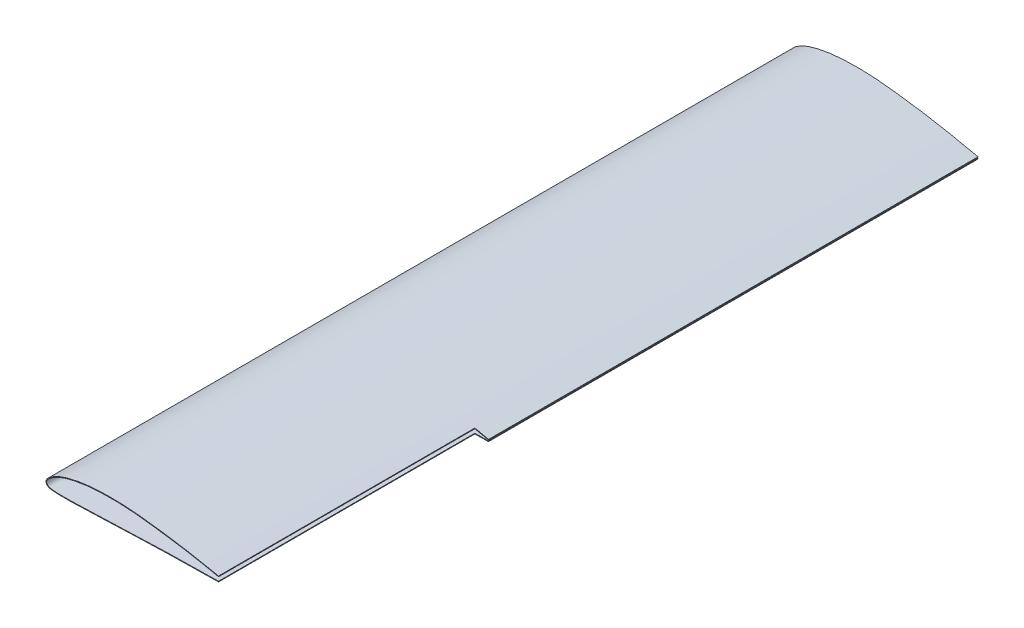
SolidWorks part; units mm, degrees
material "轻木"
ref_plane "前视基准面" through (0, 0, 0) normal (0, 0, 1) x (1, 0, 0)
ref_plane "上视基准面" through (0, 0, 0) normal (0, 1, 0) x (1, 0, 0)
ref_plane "右视基准面" through (0, 0, 0) normal (1, 0, 0) x (0, 0, -1)
other "Configuration Table"
sketch "草图2" plane through (0, 0, 0) normal (0, 0, 1) x (1, 0, 0)
  line L0 (152.0922, -4.0096) -> (151.8745, -4.9856)
  line L1 (151.8745, -6.1918) -> (151.8782, -7.1918)
  spline S0 degree 3 poles (2527.2793, 5171.2522) (1224.3818, -581.4504) (698.4321, -111.6596) (97.5228, 6.3509) (79.323, 9.677) (61.0574, 12.5697) (42.7251, 15.1223) (24.3777, 17.5567) (6.0024, 19.6713) (-12.4132, 21.2419) (-30.8708, 21.8741) (-49.3536, 21.6282) (-64.7221, 20.7846) (-76.9396, 19.4244) (-86.0445, 17.9962) (-95.0915, 16.1982) (-102.5435, 14.373) (-108.4281, 12.6438) (-112.7635, 11.1816) (-116.9506, 9.4061) (-121.0465, 7.338) (-125.0852, 5.1449) (-128.9853, 2.7585) (-131.9718, 0.5145) (-134.0254, -1.6013) (-135.3116, -3.3311) (-136.1565, -5.2223) (-136.2196, -7.0675) (-135.3796, -8.8735) (-133.9823, -10.403) (-132.2712, -11.4212) (-130.1979, -11.9075) (-127.9164, -12.2567) (-124.9055, -12.6448) (-121.1053, -12.9445) (-116.5159, -13.063) (-111.894, -13.0888) (-105.7281, -13.0822) (-98.0182, -13.0426) (-88.7886, -12.824) (-79.5455, -12.4149) (-70.2848, -12.0448) (-61.0289, -11.7236) (-48.6895, -11.3178) (-33.2723, -10.775) (-14.7708, -10.05) (3.7324, -9.2974) (22.2431, -8.606) (40.7587, -8.0244) (59.2779, -7.5768) (77.7911, -7.1821) (96.3085, -6.7893) (114.8357, -6.5452) (402.7621, -3.862) (691.0162, 21.319) (591.9409, -5930.9613) knots -2.852397 -2.852397 -2.852397 -2.852397 0.078237 0.108366 0.138495 0.168624 0.198753 0.228882 0.259011 0.28914 0.319269 0.349398 0.379527 0.394592 0.409656 0.424721 0.439785 0.447318 0.45485 0.462382 0.469915 0.477447 0.484979 0.492511 0.496277 0.500044 0.50381 0.507576 0.511342 0.515108 0.518874 0.52264 0.526407 0.530173 0.537705 0.545237 0.552769 0.560302 0.575366 0.590431 0.605495 0.62056 0.635624 0.650689 0.680818 0.710947 0.741076 0.771205 0.801334 0.831463 0.861593 0.891722 0.921851 0.95198 2.29766 2.29766 2.29766 2.29766 only from (151.8745, -4.9856) to (151.8745, -6.1918) construction
  spline S1 degree 3 poles (151.8745, -4.9856) (139.8319, -2.2996) (121.7361, 1.5957) (97.5228, 6.3509) (79.323, 9.677) (61.0574, 12.5697) (42.7251, 15.1223) (24.3777, 17.5567) (6.0024, 19.6713) (-12.4132, 21.2419) (-30.8708, 21.8741) (-49.3536, 21.6282) (-64.7221, 20.7846) (-76.9396, 19.4244) (-86.0445, 17.9962) (-95.0915, 16.1982) (-102.5435, 14.373) (-108.4281, 12.6438) (-112.7635, 11.1816) (-116.9506, 9.4061) (-121.0465, 7.338) (-125.0852, 5.1449) (-128.9853, 2.7585) (-131.9718, 0.5145) (-134.0254, -1.6013) (-135.3116, -3.3311) (-136.1565, -5.2223) (-136.2196, -7.0675) (-135.3796, -8.8735) (-133.9823, -10.403) (-132.2712, -11.4212) (-130.1979, -11.9075) (-127.9164, -12.2567) (-124.9055, -12.6448) (-121.1053, -12.9445) (-116.5159, -13.063) (-111.894, -13.0888) (-105.7281, -13.0822) (-98.0182, -13.0426) (-88.7886, -12.824) (-79.5455, -12.4149) (-70.2848, -12.0448) (-61.0289, -11.7236) (-48.6895, -11.3178) (-33.2723, -10.775) (-14.7708, -10.05) (3.7324, -9.2974) (22.2431, -8.606) (40.7587, -8.0244) (59.2779, -7.5768) (77.7911, -7.1821) (96.3085, -6.7893) (114.8357, -6.5452) (133.3464, -6.3727) (145.6993, -6.2144) (151.8745, -6.1918) knots 0.017978 0.017978 0.017978 0.017978 0.078237 0.108366 0.138495 0.168624 0.198753 0.228882 0.259011 0.28914 0.319269 0.349398 0.379527 0.394592 0.409656 0.424721 0.439785 0.447318 0.45485 0.462382 0.469915 0.477447 0.484979 0.492511 0.496277 0.500044 0.50381 0.507576 0.511342 0.515108 0.518874 0.52264 0.526407 0.530173 0.537705 0.545237 0.552769 0.560302 0.575366 0.590431 0.605495 0.62056 0.635624 0.650689 0.680818 0.710947 0.741076 0.771205 0.801334 0.831463 0.861593 0.891722 0.921851 0.95198 0.982109 0.982109 0.982109 0.982109
  spline S2 degree 1 poles (152.0922, -4.0096) (151.8782, -7.1918) knots 0 0 1 1 construction
  spline S3 degree 3 poles (152.0922, -4.0096) (140.0432, -1.3222) (121.9389, 2.575) (97.7101, 7.3332) (79.4922, 10.6627) (61.2022, 13.5592) (42.8597, 16.1132) (24.5027, 18.5489) (6.1053, 20.6662) (-12.3516, 22.2404) (-30.8624, 22.8744) (-46.299, 22.669) (-58.632, 22.1205) (-67.8671, 21.4407) (-77.0723, 20.4159) (-86.2202, 18.9809) (-95.3059, 17.1753) (-102.8005, 15.3398) (-108.7246, 13.5991) (-113.1153, 12.1187) (-117.3777, 10.3111) (-121.5119, 8.2233) (-125.5806, 6.0137) (-129.536, 3.5951) (-132.6228, 1.2783) (-134.7837, -0.9441) (-136.1671, -2.8051) (-137.1472, -4.9404) (-137.2319, -7.3047) (-136.2082, -9.4557) (-134.6385, -11.1793) (-132.6214, -12.3742) (-130.3576, -12.8949) (-128.0581, -13.2467) (-125.0072, -13.6401) (-121.1526, -13.9439) (-116.5273, -14.063) (-111.8951, -14.0888) (-105.7248, -14.0822) (-98.0062, -14.0426) (-88.7519, -13.8234) (-79.5007, -13.4139) (-70.2483, -13.0442) (-60.9957, -12.723) (-48.656, -12.3173) (-33.2349, -11.7743) (-14.7303, -11.0491) (3.772, -10.2967) (22.2778, -9.6051) (46.956, -8.8316) (71.6421, -8.3141) (96.3266, -7.7889) (114.8446, -7.5453) (133.3602, -7.3726) (145.7054, -7.2144) (151.8782, -7.1918) knots 0.017978 0.017978 0.017978 0.017978 0.078237 0.108366 0.138495 0.168624 0.198753 0.228882 0.259011 0.28914 0.319269 0.349398 0.364463 0.379527 0.394592 0.409656 0.424721 0.439785 0.447318 0.45485 0.462382 0.469915 0.477447 0.484979 0.492511 0.496277 0.500044 0.50381 0.507576 0.511342 0.515108 0.518874 0.52264 0.526407 0.530173 0.537705 0.545237 0.552769 0.560302 0.575366 0.590431 0.605495 0.62056 0.635624 0.650689 0.680818 0.710947 0.741076 0.771205 0.801334 0.861593 0.891722 0.921851 0.95198 0.982109 0.982109 0.982109 0.982109
  dimension "D1" = 1
extrude "凸台-拉伸1" add sketch "草图2" along normal blind 1158
sketch "草图3" plane through (0, 0, 1158) normal (0, 0, 1) x (1, 0, 0)
  line L0 (130.7876, -7.3898) -> (169.3921, -7.3898)
  line L1 (169.3921, -7.3898) -> (130.7876, 0.6326)
  line L2 (130.7876, 0.6326) -> (130.7876, -7.3898)
  line L3 (130.7876, -6.3897) -> (130.7876, -3.3897) construction
  spline S0 degree 3 poles (152.0922, -4.0096) (140.0432, -1.3222) (121.9389, 2.575) (97.7101, 7.3332) (79.4922, 10.6627) (61.2022, 13.5592) (42.8597, 16.1132) (24.5027, 18.5489) (6.1053, 20.6662) (-12.3516, 22.2404) (-30.8624, 22.8744) (-46.299, 22.669) (-58.632, 22.1205) (-67.8671, 21.4407) (-77.0723, 20.4159) (-86.2202, 18.9809) (-95.3059, 17.1753) (-102.8005, 15.3398) (-108.7246, 13.5991) (-113.1153, 12.1187) (-117.3777, 10.3111) (-121.5119, 8.2233) (-125.5806, 6.0137) (-129.536, 3.5951) (-132.6228, 1.2783) (-134.7837, -0.9441) (-136.1671, -2.8051) (-137.1472, -4.9404) (-137.2319, -7.3047) (-136.2082, -9.4557) (-134.6385, -11.1793) (-132.6214, -12.3742) (-130.3576, -12.8949) (-128.0581, -13.2467) (-125.0072, -13.6401) (-121.1526, -13.9439) (-116.5273, -14.063) (-111.8951, -14.0888) (-105.7248, -14.0822) (-98.0062, -14.0426) (-88.7519, -13.8234) (-79.5007, -13.4139) (-70.2483, -13.0442) (-60.9957, -12.723) (-48.656, -12.3173) (-33.2349, -11.7743) (-14.7303, -11.0491) (3.772, -10.2967) (22.2778, -9.6051) (46.956, -8.8316) (71.6421, -8.3141) (96.3266, -7.7889) (114.8446, -7.5453) (133.3602, -7.3726) (145.7054, -7.2144) (151.8782, -7.1918) knots 0.017978 0.017978 0.017978 0.017978 0.078237 0.108366 0.138495 0.168624 0.198753 0.228882 0.259011 0.28914 0.319269 0.349398 0.364463 0.379527 0.394592 0.409656 0.424721 0.439785 0.447318 0.45485 0.462382 0.469915 0.477447 0.484979 0.492511 0.496277 0.500044 0.50381 0.507576 0.511342 0.515108 0.518874 0.52264 0.526407 0.530173 0.537705 0.545237 0.552769 0.560302 0.575366 0.590431 0.605495 0.62056 0.635624 0.650689 0.680818 0.710947 0.741076 0.771205 0.801334 0.861593 0.891722 0.921851 0.95198 0.982109 0.982109 0.982109 0.982109 construction
  dimension "D1" = 38.6045
extrude "切除-拉伸1" cut sketch "草图3" against normal blind 398
